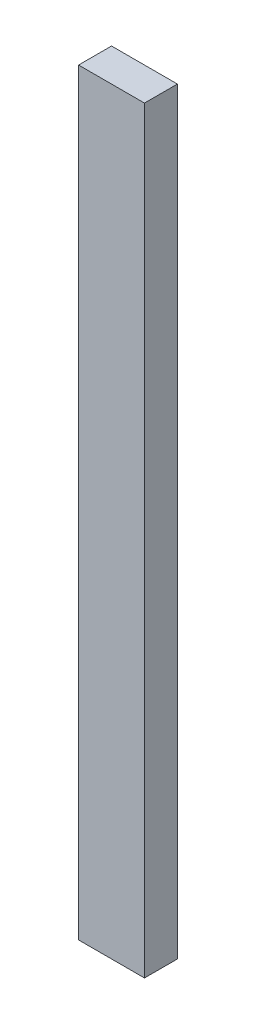
SolidWorks part; units mm, degrees
ref_plane "Front Plane" through (0, 0, 0) normal (0, 0, 1) x (1, 0, 0)
ref_plane "Top Plane" through (0, 0, 0) normal (0, 1, 0) x (1, 0, 0)
ref_plane "Right Plane" through (0, 0, 0) normal (1, 0, 0) x (0, 0, -1)
sketch "Sketch1" plane through (0, 0, 0) normal (0, 1, 0) x (1, 0, 0)
  line L1 (0, 0) -> (25.4, 0)
  line L2 (0, 0) -> (0, 12.7)
  line L3 (0, 12.7) -> (25.4, 12.7)
  line L4 (25.4, 0) -> (25.4, 12.7)
  dimension "D1" = 12.7
  dimension "D2" = 25.4
extrude "Boss-Extrude1" add sketch "Sketch1" along normal blind 292.1
